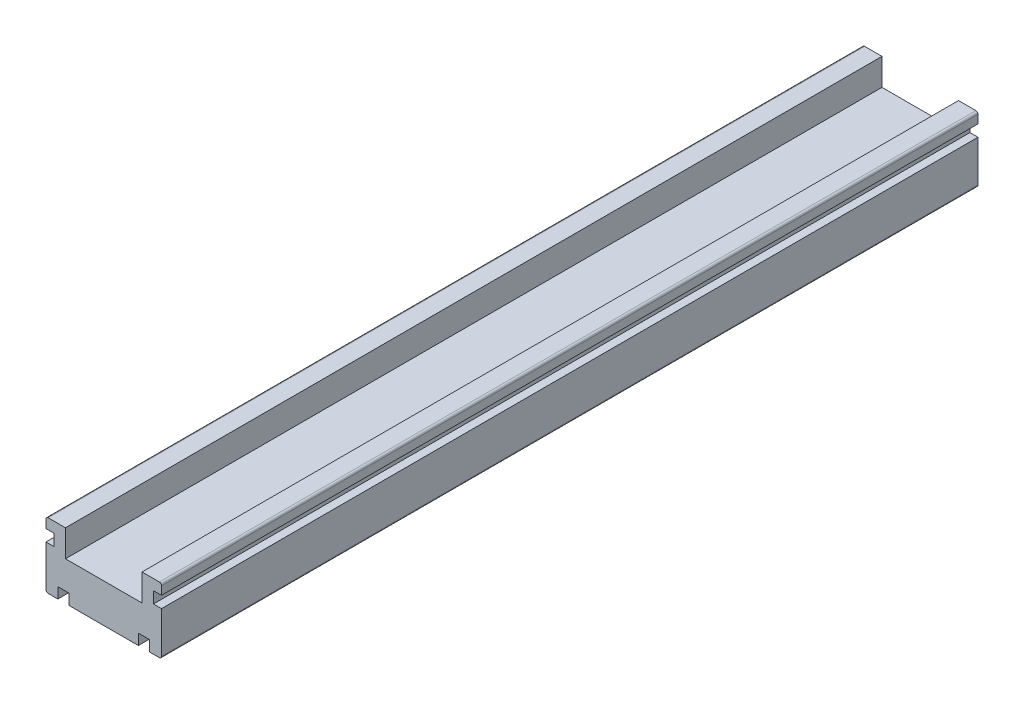
SolidWorks part; units mm, degrees
ref_plane "Front Plane" through (0, 0, 0) normal (0, 0, 1) x (1, 0, 0)
ref_plane "Top Plane" through (0, 0, 0) normal (0, 1, 0) x (1, 0, 0)
ref_plane "Right Plane" through (0, 0, 0) normal (1, 0, 0) x (0, 0, -1)
sketch "Sketch1" plane through (0, 0, 0) normal (0, 0, 1) x (1, 0, 0)
  line L1 (-21.5, -12.2) -> (21.5, -12.2)
  line L2 (-21.5, -12.2) -> (-21.5, 12.2)
  line L3 (-21.5, 12.2) -> (21.5, 12.2)
  line L4 (21.5, -12.2) -> (21.5, 12.2)
  line L5 (-21.5, -12.2) -> (21.5, 12.2) construction
  line L6 (-21.5, 12.2) -> (21.5, -12.2) construction
  point P0 (0, 0)
  dimension "D1" = 43
  dimension "D2" = 24.4
extrude "Boss-Extrude1" add sketch "Sketch1" along normal blind 304
fillet "Fillet1" radius 0.8 4 edges at (21.5, -12.2, 152) (-21.5, -12.2, 152) (-21.5, 12.2, 152) (21.5, 12.2, 152)
sketch "Sketch3" plane through (0, 0, 0) normal (0, 0, -1) x (-1, 0, 0)
  line L0 (-21.5, -11.4) -> (-21.5, 11.4) construction
  line L1 (-21.5, 8.3) -> (-18.5, 8.3)
  line L2 (-21.5, 8.3) -> (-21.5, 4)
  line L3 (-21.5, 4) -> (-18.5, 4)
  line L4 (-18.5, 8.3) -> (-18.5, 4)
  line L5 (0, 12.2) -> (0, -12.2) construction
  line L6 (-20.7, 12.2) -> (20.7, 12.2) construction
  line L7 (20.7, -12.2) -> (-20.7, -12.2) construction
  line L8 (18.5, 8.3) -> (18.5, 4)
  line L9 (21.5, 4) -> (18.5, 4)
  line L10 (21.5, 8.3) -> (21.5, 4)
  line L11 (21.5, 8.3) -> (18.5, 8.3)
  dimension "D1" = 4.3
  dimension "D2" = 16.2
  dimension "D3" = 3
extrude "Cut-Extrude1" cut sketch "Sketch3" against normal through all
sketch "Sketch5" plane through (0, 0, 0) normal (0, 0, -1) x (-1, 0, 0)
  line L0 (-14.25, 12.2) -> (-14.25, 2.2)
  line L1 (-20.7, 12.2) -> (20.7, 12.2) construction
  line L2 (-14.25, 2.2) -> (14.25, 2.2)
  line L3 (14.25, 2.2) -> (14.25, 12.2)
  line L4 (14.25, 12.2) -> (-14.25, 12.2)
  line L5 (0, 0) -> (0, 12.2) construction
  dimension "D1" = 28.5
  dimension "D2" = 10
extrude "Cut-Extrude2" cut sketch "Sketch5" against normal through all
sketch "Sketch6" plane through (0, 0, 0) normal (0, 0, -1) x (-1, 0, 0)
  line L0 (20.7, -12.2) -> (-20.7, -12.2) construction
  line L1 (-17.1, -16.2) -> (-12.9, -16.2)
  line L2 (-17.1, -16.2) -> (-17.1, -8.2)
  line L3 (-17.1, -8.2) -> (-12.9, -8.2)
  line L4 (-12.9, -16.2) -> (-12.9, -8.2)
  line L5 (-17.1, -16.2) -> (-12.9, -8.2) construction
  line L6 (-17.1, -8.2) -> (-12.9, -16.2) construction
  line L7 (-21.5, -11.4) -> (-21.5, 4) construction
  line L8 (12.9, -16.2) -> (17.1, -16.2)
  line L9 (12.9, -16.2) -> (12.9, -8.2)
  line L10 (12.9, -8.2) -> (17.1, -8.2)
  line L11 (17.1, -16.2) -> (17.1, -8.2)
  line L12 (12.9, -16.2) -> (17.1, -8.2) construction
  line L13 (12.9, -8.2) -> (17.1, -16.2) construction
  line L14 (21.5, 4) -> (21.5, -11.4) construction
  point P0 (-15, -12.2)
  point P7 (15, -12.2)
  dimension "D1" = 4.4
  dimension "D2" = 4.4
  dimension "D3" = 4.2
  dimension "D4" = 4
extrude "Cut-Extrude3" cut sketch "Sketch6" against normal through all
equation "\"D2@Sketch6\"=\"D1@Sketch6\""
